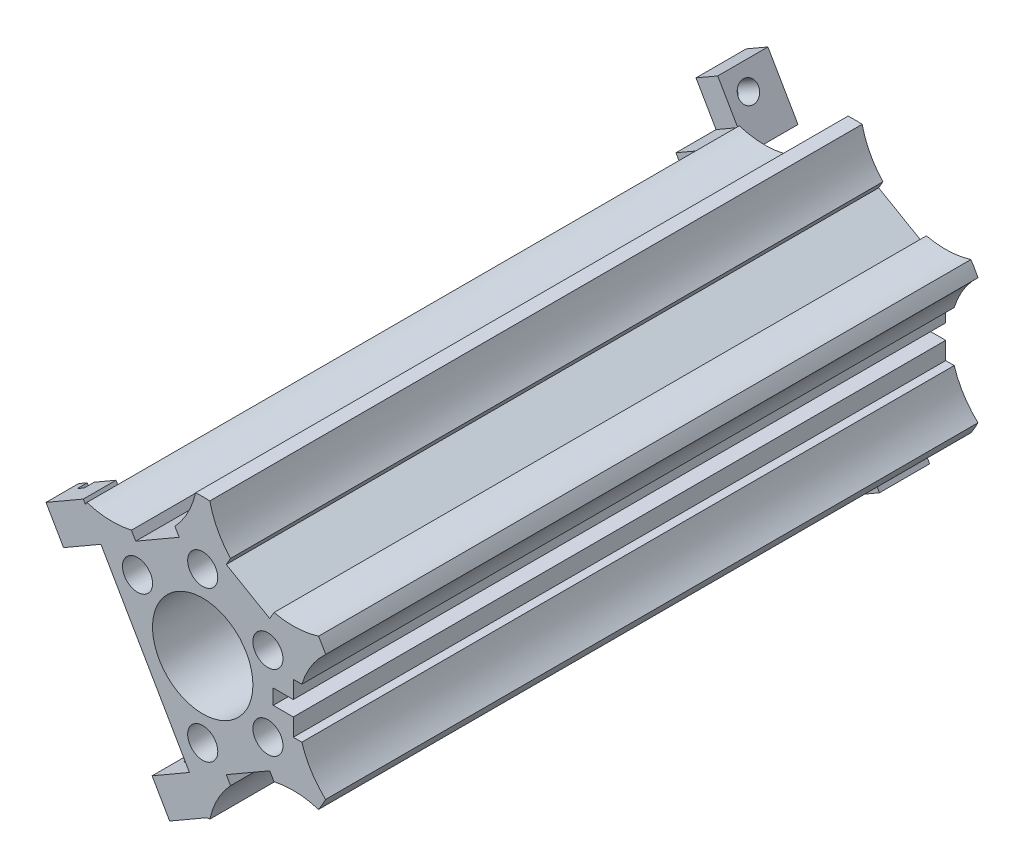
SolidWorks part; units mm, degrees
ref_plane "Plan de face" through (0, 0, 0) normal (0, 0, 1) x (1, 0, 0)
ref_plane "Plan de dessus" through (0, 0, 0) normal (0, 1, 0) x (1, 0, 0)
ref_plane "Plan de droite" through (0, 0, 0) normal (1, 0, 0) x (0, 0, -1)
sketch "Esquisse1" plane through (0, 0, 0) normal (0, 0, 1) x (1, 0, 0)
  line L0 (-36, 0) -> (36, 0) construction
  line L2 (0, 0) -> (0, -53.5) construction
  line L4 (-31.4635, 18.3063) -> (31.5363, 18.1806) construction
  line L5 (-31.4635, 18.3063) -> (-31.4137, 43.3063) construction
  line L6 (-31.4137, 43.3063) -> (31.5862, 43.1806) construction
  line L7 (31.5363, 18.1806) -> (31.5862, 43.1806) construction
  line L8 (-50.7224, 8.5) -> (-36, 0) construction
  line L9 (-36, 0) -> (-50.7224, -8.5) construction
  line L12 (-18, -51.1769) -> (-18, -48.1769)
  line L17 (-34.5498, -19.9474) -> (0, 0) construction
  line L19 (-50.7224, 8.5) -> (-53.3205, 10)
  line L20 (-32.7224, 39.6769) -> (-35.3205, 41.1769)
  line L21 (-18, 51.1769) -> (-18, 48.1769)
  line L23 (-50.7224, -8.5) -> (-53.3205, -10)
  line L25 (-32.7224, -39.6769) -> (-35.3205, -41.1769)
  line L26 (50.7224, -8.5) -> (53.3205, -10)
  line L27 (32.7224, -39.6769) -> (35.3205, -41.1769)
  line L28 (18, -51.1769) -> (18, -48.1769)
  line L30 (18, 51.1769) -> (18, 48.1769)
  line L31 (32.7224, 39.6769) -> (35.3205, 41.1769)
  line L32 (50.7224, 8.5) -> (53.3205, 10)
  circle A0 centre (0, 0) radius 18 construction
  circle A1 centre (36, 0) radius 18 construction
  circle A2 centre (-36, 0) radius 18 construction
  circle A3 centre (-18, -31.1769) radius 18 construction
  circle A4 centre (18, -31.1769) radius 18 construction
  circle A6 centre (0, 0) radius 53.5 construction
  circle A7 centre (0, 0) radius 17 construction
  circle A8 centre (36, 0) radius 17 construction
  circle A11 centre (18, -31.1769) radius 17 construction
  arc A12 (-50.7224, 8.5) -> (-50.7224, -8.5) centre (-36, 0) cw
  circle A24 centre (-36, 0) radius 20 construction
  arc A25 (-53.3205, -10) -> (-34.5498, -19.9474) centre (-36, 0) ccw
  arc A26 (-18, -48.1769) -> (-32.7224, -39.6769) centre (-18, -31.1769) ccw
  arc A27 (-35.3205, -41.1769) -> (-34.5498, -19.9474) centre (-18, -31.1769) cw
  arc A29 (-18, -51.1769) -> (0, -39.8947) centre (-18, -31.1769) ccw
  arc A32 (53.3205, -10) -> (34.5498, -19.9474) centre (36, 0) cw
  arc A33 (35.3205, -41.1769) -> (34.5498, -19.9474) centre (18, -31.1769) ccw
  arc A34 (18, -48.1769) -> (32.7224, -39.6769) centre (18, -31.1769) cw
  arc A35 (18, -51.1769) -> (0, -39.8947) centre (18, -31.1769) cw
  arc A36 (-53.3205, 10) -> (-34.5498, 19.9474) centre (-36, 0) cw
  arc A37 (-35.3205, 41.1769) -> (-34.5498, 19.9474) centre (-18, 31.1769) ccw
  arc A38 (-18, 48.1769) -> (-32.7224, 39.6769) centre (-18, 31.1769) cw
  arc A39 (-18, 51.1769) -> (0, 39.8947) centre (-18, 31.1769) cw
  arc A40 (18, 51.1769) -> (0, 39.8947) centre (18, 31.1769) ccw
  arc A41 (18, 48.1769) -> (32.7224, 39.6769) centre (18, 31.1769) ccw
  arc A42 (35.3205, 41.1769) -> (34.5498, 19.9474) centre (18, 31.1769) cw
  arc A43 (53.3205, 10) -> (34.5498, 19.9474) centre (36, 0) ccw
  arc A44 (50.7224, -8.5) -> (50.7224, 8.5) centre (36, 0) cw
  point P48 (0, 0)
  point P61 (0, 0)
  point P69 (0, 0)
  dimension "D1" = 36
  dimension "D2" = 3
  dimension "D5" = 17
  dimension "D6" = 17
  dimension "D7" = 60
  dimension "D8" = 36
  dimension "D9" = 20
  dimension "D10" = 3
  dimension "D11" = 2
  dimension "D13" = 107
  dimension "D3" = 63
  dimension "D4" = 25
extrude "Boss.-Extru.1" add sketch "Esquisse1" along normal blind 130
sketch "Esquisse4" plane through (0, 0, 130) normal (0, 0, 1) x (1, 0, 0)
  circle A3 centre (0, 0) radius 27.5
  circle A5 centre (0, 0) radius 54.2501
  dimension "D1" = 55
extrude "Enlèv. mat.-Extru.1" cut sketch "Esquisse4" against normal through all
sketch "Esquisse5" plane through (0, 0, 130) normal (0, 0, 1) x (1, 0, 0)
  line L0 (14.2061, -14.6057) -> (5.5458, -19.6057)
  line L1 (18.0519, 5) -> (19.7519, 5)
  line L2 (18.0519, 5) -> (18.0519, -5) construction
  line L3 (18.0519, -5) -> (19.7519, -5)
  line L4 (19.7519, 5) -> (19.7519, -5)
  line L5 (4.6958, -18.1334) -> (5.5458, -19.6057)
  line L6 (13.3561, -13.1334) -> (4.6958, -18.1334)
  line L7 (13.3561, -13.1334) -> (14.2061, -14.6057)
  line L8 (-5.5458, -19.6057) -> (-14.2061, -14.6057) construction
  line L9 (-13.3561, -13.1334) -> (-14.2061, -14.6057) construction
  line L10 (-4.6958, -18.1334) -> (-13.3561, -13.1334) construction
  line L11 (-4.6958, -18.1334) -> (-5.5458, -19.6057) construction
  line L12 (-19.7519, -5) -> (-19.7519, 5) construction
  line L13 (-18.0519, 5) -> (-19.7519, 5) construction
  line L14 (-18.0519, -5) -> (-18.0519, 5) construction
  line L15 (-18.0519, -5) -> (-19.7519, -5) construction
  line L16 (-14.2061, 14.6057) -> (-5.5458, 19.6057)
  line L17 (-4.6958, 18.1334) -> (-5.5458, 19.6057)
  line L18 (-13.3561, 13.1334) -> (-4.6958, 18.1334)
  line L19 (-13.3561, 13.1334) -> (-14.2061, 14.6057)
  line L20 (5.5458, 19.6057) -> (14.2061, 14.6057)
  line L21 (13.3561, 13.1334) -> (14.2061, 14.6057)
  line L22 (4.6958, 18.1334) -> (13.3561, 13.1334)
  line L23 (4.6958, 18.1334) -> (5.5458, 19.6057)
  line L24 (0, 15) -> (0, 0) construction
  line L25 (18.0519, 5) -> (18.0519, 1.5)
  line L26 (18.0519, 1.5) -> (14.0519, 1.5)
  line L27 (14.0519, 1.5) -> (14.0519, -1.5)
  line L28 (14.0519, -1.5) -> (18.0519, -1.5)
  line L29 (18.0519, -1.5) -> (18.0519, -5)
  line L30 (0, 0) -> (18.0519, 0) construction
  line L31 (-12.9904, 7.5) -> (12.9904, -7.5) construction
  line L32 (0.9865, -27.7086) -> (-23.5031, 14.7086)
  line L33 (-23.5031, 14.7086) -> (-40.8236, 4.7086)
  line L34 (-40.8236, 4.7086) -> (-16.334, -37.7086)
  line L35 (-16.334, -37.7086) -> (0.9865, -27.7086)
  line L36 (0, -15) -> (-12.9904, 7.5) construction
  arc A0 (24.4896, 12.5104) -> (24.4896, -12.5104) centre (36, 0) ccw construction
  circle A1 centre (0, 0) radius 10
  circle A2 centre (0, 15) radius 3
  circle A3 centre (12.9904, 7.5) radius 3
  circle A4 centre (12.9904, -7.5) radius 3
  circle A5 centre (0, -15) radius 3
  circle A6 centre (-12.9904, 7.5) radius 3
  point P29 (0, 0)
  point P42 (0, 0)
  point P47 (-36.498, 9.4534)
  point P50 (0, 0)
  dimension "D3" = 20
  dimension "D4" = 6
  dimension "D6" = 4
  dimension "D11" = 13
  dimension "D1" = 1.7
  dimension "D2" = 10
  dimension "D5" = 15
  dimension "D7" = 6
  dimension "D8" = 3
  dimension "D9" = 3
  dimension "D10" = 4
  dimension "D12" = 20
extrude "Enlèv. mat.-Extru.2" cut sketch "Esquisse5" against normal through all
sketch "Esquisse7" plane through (-11.2583, -6.5, 0) normal (-0.866, -0.5, 0) x (0, 0, 1)
  line L0 (8, 24.2332) -> (0, 24.2332)
  line L5 (65, 25.0455) -> (65, -46.9545) construction
  line L6 (130, 25.0455) -> (0, 25.0455) construction
  line L7 (0, -46.9545) -> (130, -46.9545) construction
  line L8 (0, 0) -> (130, 0) construction
  line L9 (130, -24.2332) -> (130, 24.2332) construction
  line L24 (0, 24.2332) -> (0, 32.2332)
  line L29 (0, 32.2332) -> (-10, 32.2332)
  line L30 (-10, 32.2332) -> (-10, -32.2332)
  line L31 (-10, -32.2332) -> (0, -32.2332)
  line L32 (0, -32.2332) -> (0, -24.2332)
  line L34 (0, -24.2332) -> (8, -24.2332)
  line L35 (8, 24.2332) -> (8, -24.2332)
  line L36 (130, 24.2332) -> (0, 24.2332) construction
  line L37 (0, -24.2332) -> (0, 24.2332) construction
  line L38 (0, -24.2332) -> (130, -24.2332) construction
  point P0 (0, -24.2332)
  point P25 (8.8415, -24.0455)
  point P27 (0, 0)
  point P28 (8.6106, -24.0455)
  dimension "D4" = 8
  dimension "D5" = 10
  dimension "D6" = 8
  dimension "D7" = 64.4665
extrude "Boss.-Extru.2" add sketch "Esquisse7" along normal blind 5
sketch "Esquisse6" plane through (-11.2583, -6.5, 0) normal (-0.866, -0.5, 0) x (0, 0, 1)
  line L0 (0, 0) -> (130, 0) construction
  line L1 (-4, 28) -> (-4, -28) construction
  line L2 (130, -24.2332) -> (130, 24.2332) construction
  circle A2 centre (-4, 28) radius 2
  circle A3 centre (-4, -28) radius 2
  point P4 (130, 0)
  point P5 (0, 0)
  dimension "D2" = 4
  dimension "D4" = 56
  dimension "D5" = 8
extrude "Enlèv. mat.-Extru.3" cut sketch "Esquisse6" along normal through all
sketch "Esquisse8" plane through (12.1166, -20.9866, 0) normal (0.5, -0.866, 0) x (0.866, 0.5, 0)
  line L0 (-13, 130) -> (-21.6, 130)
  line L1 (-21.6, 130) -> (-21.6, 123.5)
  line L2 (-21.6, 123.5) -> (-19.6, 123.5)
  line L3 (-19.6, 123.5) -> (-19.6, 125.5)
  line L4 (-19.6, 125.5) -> (-18, 125.5)
  line L5 (-18, 125.5) -> (-18, 123.5)
  line L6 (-18, 123.5) -> (-13, 123.5)
  line L8 (-13, 130) -> (-13, 123.5)
  line L9 (-18, 0) -> (-18, 8) construction
  point P10 (-13, 123.5)
  point P11 (0, 0)
  point P13 (0, 0)
  point P14 (-13, 130)
  dimension "D1" = 6.5
  dimension "D2" = 2
  dimension "D3" = 1.6
  dimension "D4" = 2
extrude "Boss.-Extru.3" add sketch "Esquisse8" against normal up to vertex (49.2788 mm away)
sketch "Esquisse9" plane through (-18.7061, -10.8, 0) normal (-0.866, -0.5, 0) x (0, 0, 1)
  line L0 (123.5, 24.2332) -> (123.5, -24.2332) construction
  line L1 (123.5, 18.0455) -> (130, 18.0455)
  line L2 (123.5, 18.0455) -> (123.5, -17.2332)
  line L3 (123.5, -17.2332) -> (130, -17.2332)
  line L4 (130, 18.0455) -> (130, -17.2332)
  line L5 (130, 25.0455) -> (130, -24.2332) construction
  line L6 (-10, 32.2332) -> (-10, -32.2332) construction
  line L7 (-10, 20.2332) -> (8, 20.2332)
  line L8 (-10, 20.2332) -> (-10, -20.2332)
  line L9 (-10, -20.2332) -> (8, -20.2332)
  line L10 (8, 20.2332) -> (8, -20.2332)
  line L11 (8, -24.2332) -> (8, 24.2332) construction
  line L12 (130, 25.0455) -> (123.5, 25.0455) construction
  line L13 (130, -24.2332) -> (123.5, -24.2332) construction
  line L14 (0, 32.2332) -> (-10, 32.2332) construction
  line L15 (-10, -32.2332) -> (0, -32.2332) construction
  dimension "D1" = 7
  dimension "D2" = 7
  dimension "D3" = 12
  dimension "D4" = 12
extrude "Enlèv. mat.-Extru.4" cut sketch "Esquisse9" against normal up to vertex
